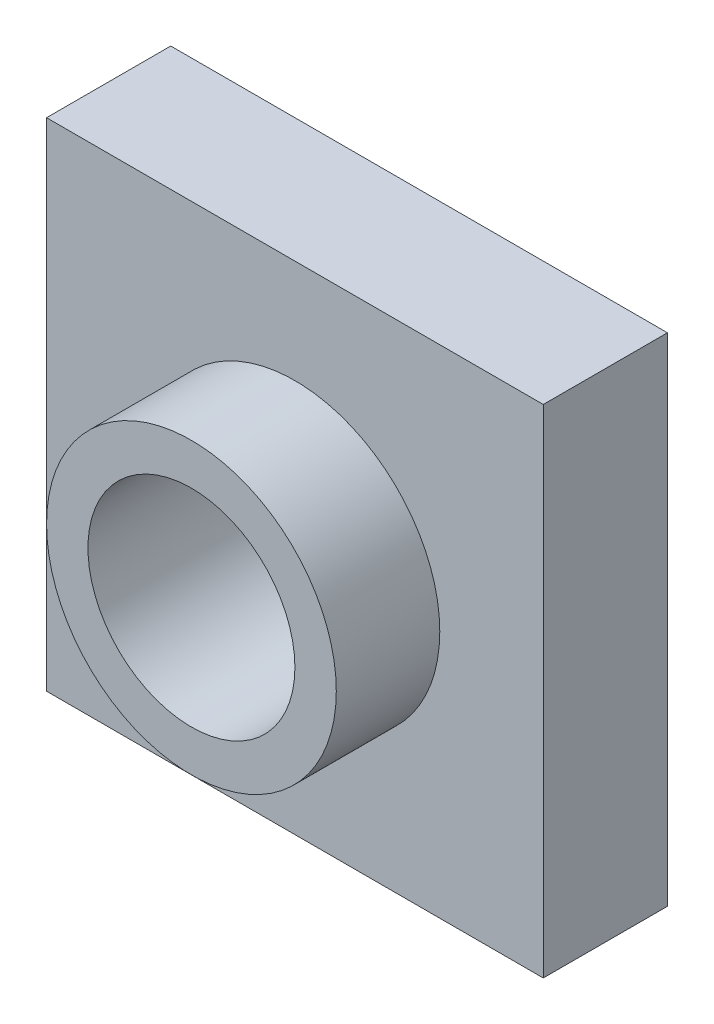
SolidWorks part; units mm, degrees
ref_plane "前基準面" through (0, 0, 0) normal (0, 0, 1) x (1, 0, 0)
ref_plane "上基準面" through (0, 0, 0) normal (0, 1, 0) x (1, 0, 0)
ref_plane "右基準面" through (0, 0, 0) normal (1, 0, 0) x (0, 0, -1)
sketch "草圖1" plane through (0, 0, 0) normal (0, 0, 1) x (1, 0, 0)
  line L1 (0, 0) -> (120, 0)
  line L2 (0, 0) -> (0, 120)
  line L3 (0, 120) -> (120, 120)
  line L4 (120, 0) -> (120, 120)
  circle A0 centre (60, 60) radius 25
  point P9 (71.0543, 120)
  point P10 (58.6464, 60.7896)
  dimension "D5" = 50
  dimension "D1" = 120
  dimension "D2" = 120
  dimension "D3" = 60
  dimension "D4" = 60
extrude "填料-伸長1" add sketch "草圖1" along normal blind 30
sketch "草圖2" plane through (0, 0, 30) normal (0, 0, 1) x (1, 0, 0)
  line L0 (120, 0) -> (120, 120) construction
  line L1 (0, 0) -> (120, 0) construction
  circle A0 centre (60, 60) radius 35
  circle A2 centre (60, 60) radius 25
  dimension "D1" = 70
  dimension "D4" = 10
  dimension "D2" = 60
  dimension "D3" = 60
extrude "填料-伸長2" add sketch "草圖2" along normal blind 25
